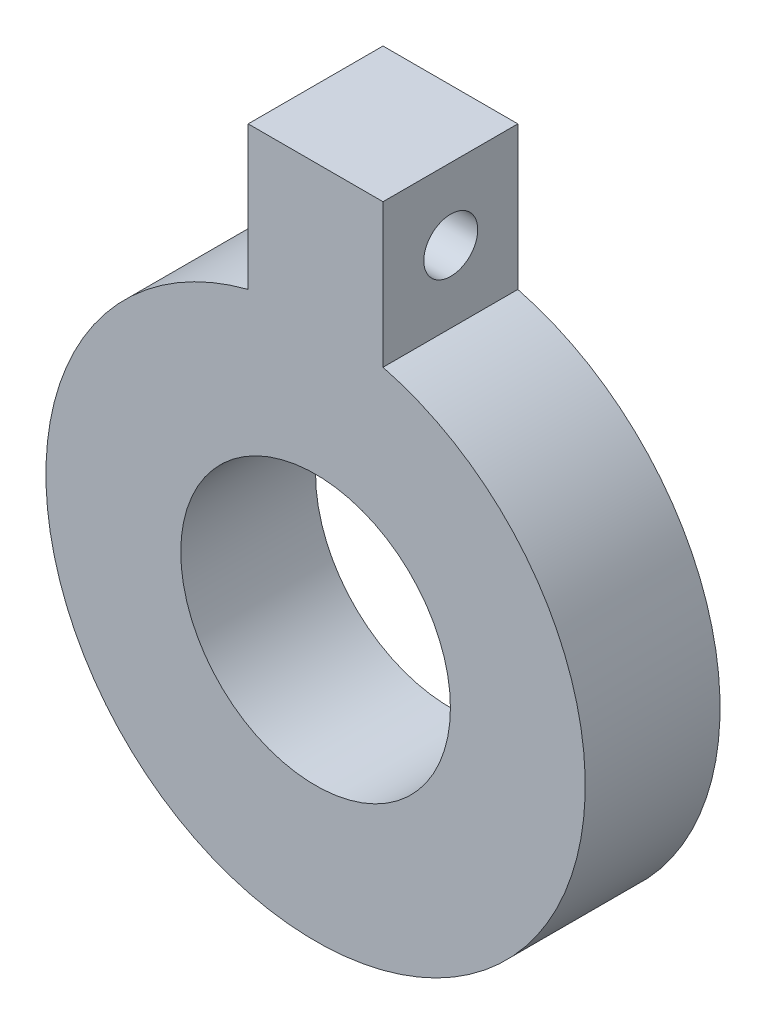
SolidWorks part; units mm, degrees
ref_plane "Plan de face" through (0, 0, 0) normal (0, 0, 1) x (1, 0, 0)
ref_plane "Plan de dessus" through (0, 0, 0) normal (0, 1, 0) x (1, 0, 0)
ref_plane "Plan de droite" through (0, 0, 0) normal (1, 0, 0) x (0, 0, -1)
sketch "Esquisse1" plane through (0, 0, 0) normal (0, 0, 1) x (1, 0, 0)
  circle A0 centre (0, 0) radius 5
  circle A1 centre (0, 0) radius 10
  dimension "D1" = 10
  dimension "D2" = 20
extrude "Boss.-Extru.1" add sketch "Esquisse1" along normal blind 5
sketch "Esquisse2" plane through (0, 0, 5) normal (0, 0, 1) x (1, 0, 0)
  line L12 (27.2852, 0) -> (-27.2852, 0) construction
  line L26 (0, 20.4609) -> (0, -20.4609) construction
  line L39 (2.5, 8) -> (-2.5, 8)
  line L40 (2.5, 8) -> (2.5, 15)
  line L41 (-2.5, 8) -> (-2.5, 15)
  line L42 (2.5, 15) -> (-2.5, 15)
  point P0 (0, 15)
  dimension "D1" = 5
  dimension "D2" = 7
  dimension "D3" = 8
extrude "Boss.-Extru.2" add sketch "Esquisse2" against normal blind 5
sketch "Esquisse3" plane through (-2.5, 0, 0) normal (-1, 0, 0) x (0, -1, 0)
  circle A0 centre (-12.3459, 2.4874) radius 1
  point P2 (-12.8264, 7.5654)
  point P3 (-12.3459, 2.4874)
  dimension "D1" = 2
extrude "Enlèv. mat.-Extru.1" cut sketch "Esquisse3" against normal blind 10
